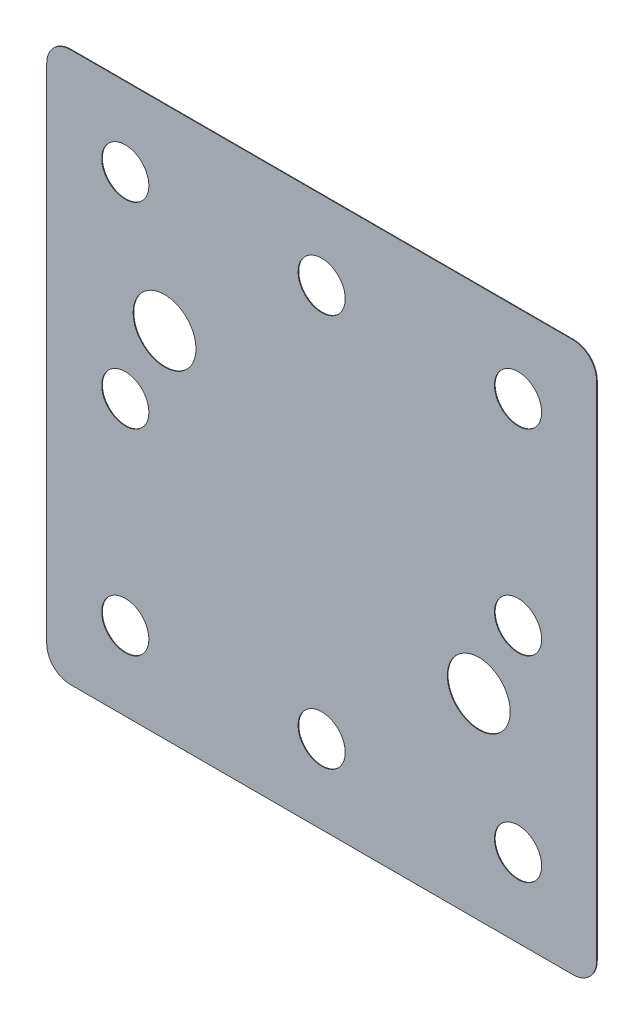
SolidWorks part; units mm, degrees
ref_plane "Front Plane" through (0, 0, 0) normal (0, 0, 1) x (1, 0, 0)
ref_plane "Top Plane" through (0, 0, 0) normal (0, 1, 0) x (1, 0, 0)
ref_plane "Right Plane" through (0, 0, 0) normal (1, 0, 0) x (0, 0, -1)
sketch "Sketch1" plane through (0, 0, 0) normal (0, 0, 1) x (1, 0, 0)
  line L1 (-35, -35) -> (35, -35)
  line L2 (-35, -35) -> (-35, 35)
  line L3 (-35, 35) -> (35, 35)
  line L4 (35, -35) -> (35, 35)
  line L5 (0, 35) -> (0, -35) construction
  line L6 (-35, 0) -> (35, 0) construction
  point P0 (0, 0)
  dimension "D1" = 70
  dimension "D2" = 70
extrude "Boss-Extrude1" add sketch "Sketch1" along normal blind 0.08
sketch "Sketch2" plane through (0, 0, 0.08) normal (0, 0, 1) x (1, 0, 0)
  circle A5 centre (-25, -25) radius 3
  circle A9 centre (25, 25) radius 3
  circle A10 centre (25, 0) radius 3
  circle A11 centre (25, -25) radius 3
  circle A12 centre (0, -25) radius 3
  circle A13 centre (-25, -25) radius 3
  circle A14 centre (-25, 0) radius 3
  circle A15 centre (-25, 25) radius 3
  circle A16 centre (0, 25) radius 3
  point P0 (0, 0)
  point P12 (0, 0)
  dimension "D3" = 50
  dimension "D4" = 50
extrude "Cut-Extrude1" cut sketch "Sketch2" against normal blind 10 contours A16 | A9 | A10 | A14 | A15 | A5 | A12 | A11
sketch "Sketch3" plane through (0, 0, 0) normal (0, 0, -1) x (-1, 0, 0)
  line L5 (-15, -15) -> (15, -15)
  line L6 (-15, -15) -> (-15, 15)
  line L7 (-15, 15) -> (15, 15)
  line L8 (15, -15) -> (15, 15)
  line L9 (0, 15) -> (0, -15) construction
  line L10 (-15, 0) -> (15, 0) construction
  line L15 (0, 20) -> (0, -20) construction
  line L16 (-20, 0) -> (20, 0) construction
  circle A0 centre (-20, -10) radius 4
  circle A1 centre (20, 10) radius 4
  point P0 (0, 0)
  point P4 (0, 0)
  dimension "D5" = 10
  dimension "D1" = 30
  dimension "D2" = 30
  dimension "D6" = 10
fillet "Fillet1" radius 3 4 edges at (-35, -35, 0.04) (35, -35, 0.04) (35, 35, 0.04) (-35, 35, 0.04)
extrude "Cut-Extrude2" cut sketch "Sketch3" against normal blind 10 contours A1 | A0
